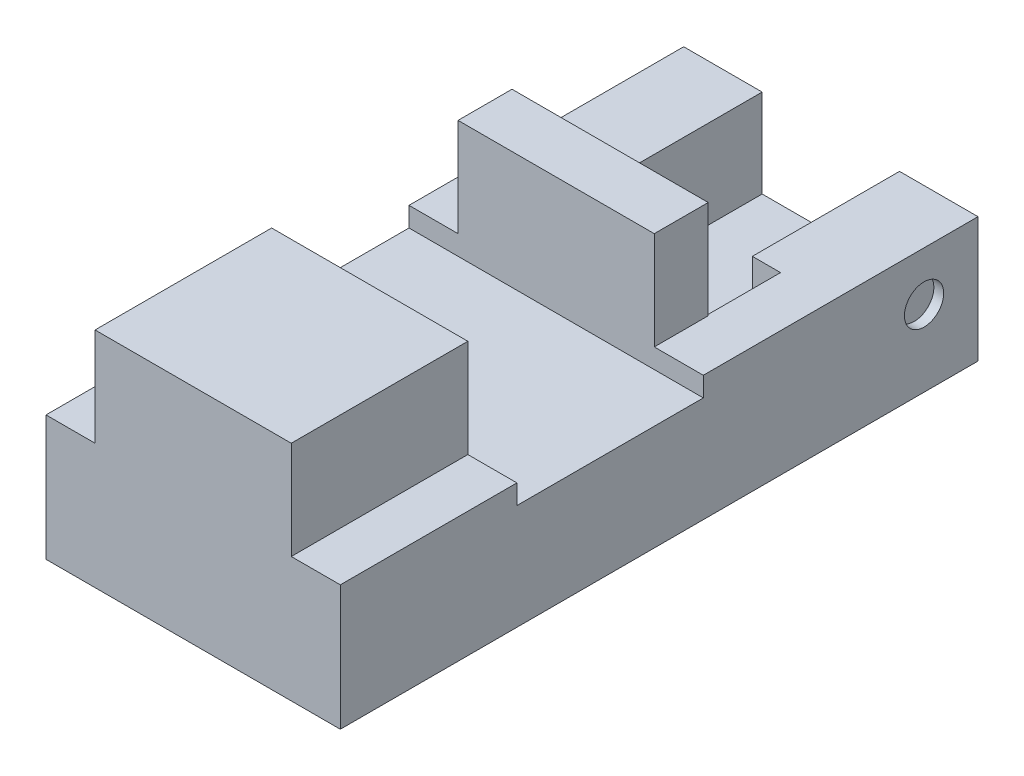
SolidWorks part; units mm, degrees
ref_plane "Front Plane" through (0, 0, 0) normal (0, 0, 1) x (1, 0, 0)
ref_plane "Top Plane" through (0, 0, 0) normal (0, 1, 0) x (1, 0, 0)
ref_plane "Right Plane" through (0, 0, 0) normal (1, 0, 0) x (0, 0, -1)
sketch "Sketch1" plane through (0, 0, 0) normal (0, 1, 0) x (1, 0, 0)
  line L0 (-1.4, 3) -> (-1.4, 0)
  line L1 (-1.4, 0) -> (-1.975, 0)
  line L2 (-1.975, 0) -> (-1.975, -1.5)
  line L4 (-3, -10) -> (-3, 3)
  line L5 (-3, 3) -> (-1.4, 3)
  line L6 (1.4, 0) -> (1.4, 3)
  line L7 (1.4, 3) -> (3, 3)
  line L8 (3, 3) -> (3, -10)
  line L10 (1.975, -1.5) -> (1.975, 0)
  line L11 (1.975, 0) -> (1.4, 0)
  line L12 (-1.4, 0) -> (1.4, 0) construction
  line L13 (-1.975, -1.5) -> (1.975, -1.5)
  line L14 (-3, -10) -> (3, -10)
  dimension "D1" = 2.8
  dimension "D2" = 3.95
  dimension "D3" = 3
  dimension "D5" = 6
  dimension "D6" = 1.5
  dimension "D7" = 10
extrude "Boss-Extrude1" add sketch "Sketch1" along normal blind 1.8
sketch "Sketch2" plane through (0, 0, 0) normal (0, -1, 0) x (1, 0, 0)
  line L0 (-3, 10) -> (3, 10) construction
  line L1 (-3, 10) -> (3, 10)
  line L2 (-3, -3) -> (-3, 10) construction
  line L3 (-3, -3) -> (-3, 10)
  line L4 (3, 10) -> (3, -3) construction
  line L5 (3, 10) -> (3, -3)
  line L6 (-3, -3) -> (3, -3)
extrude "Boss-Extrude2" add sketch "Sketch2" along normal blind 0.75
sketch "Sketch7" plane through (0, 1.8, 0) normal (0, 1, 0) x (1, 0, 0)
  line L0 (-3, 3) -> (-3, -10) construction
  line L4 (-3, -2.6) -> (-3, -6.4)
  line L5 (3, -10) -> (3, 3) construction
  line L6 (-3, -6.4) -> (3, -6.4)
  line L8 (-3, -2.6) -> (3, -2.6)
  line L9 (3, -6.4) -> (3, -2.6)
  line L10 (1.35, -2.6) -> (-1.35, -2.6) construction
  point P0 (-3.0539, -6.4)
extrude "Cut-Extrude2" cut sketch "Sketch7" against normal blind 0.4
sketch "Sketch9" plane through (3, 0, 0) normal (1, 0, 0) x (0, 0, -1)
  line L0 (-2.6, 1.8) -> (3, 1.8) construction
  line L1 (3, 1.8) -> (3, -0.75) construction
  circle A0 centre (1.9, 0.8) radius 0.4
  dimension "D1" = 0.8
  dimension "D2" = 1
  dimension "D3" = 1.1
extrude "Cut-Extrude4" cut sketch "Sketch9" against normal blind 0.2
mirror "Mirror1" about plane through (0, 0, 0) normal (1, 0, 0) of "Cut-Extrude4"
sketch "Sketch10" plane through (0, 1.8, 0) normal (0, 1, 0) x (1, 0, 0)
  line L1 (-2, -2.6) -> (2, -2.6)
  line L3 (-2, -1.5) -> (2, -1.5)
  line L12 (1.975, -1.5) -> (-1.975, -1.5) construction
  line L13 (-3, -6.4) -> (-1.35, -6.4) construction
  line L14 (-2, -6.4) -> (2, -6.4)
  line L15 (-3, -10) -> (3, -10) construction
  line L16 (-2, -10) -> (2, -10)
  line L18 (-2, -1.5) -> (-2, -2.6)
  line L19 (-1.35, -2.6) -> (-3, -2.6) construction
  line L20 (2, -10) -> (2, -6.4)
  line L21 (2, -2.6) -> (2, -1.5)
  line L22 (-2, -6.4) -> (-2, -10)
  line L23 (-2, -1.5) -> (2, -2.6) construction
  point P18 (0, -2.05)
  point P19 (0, 0)
  dimension "D1" = 4
extrude "Boss-Extrude3" add sketch "Sketch10" along normal blind 2
